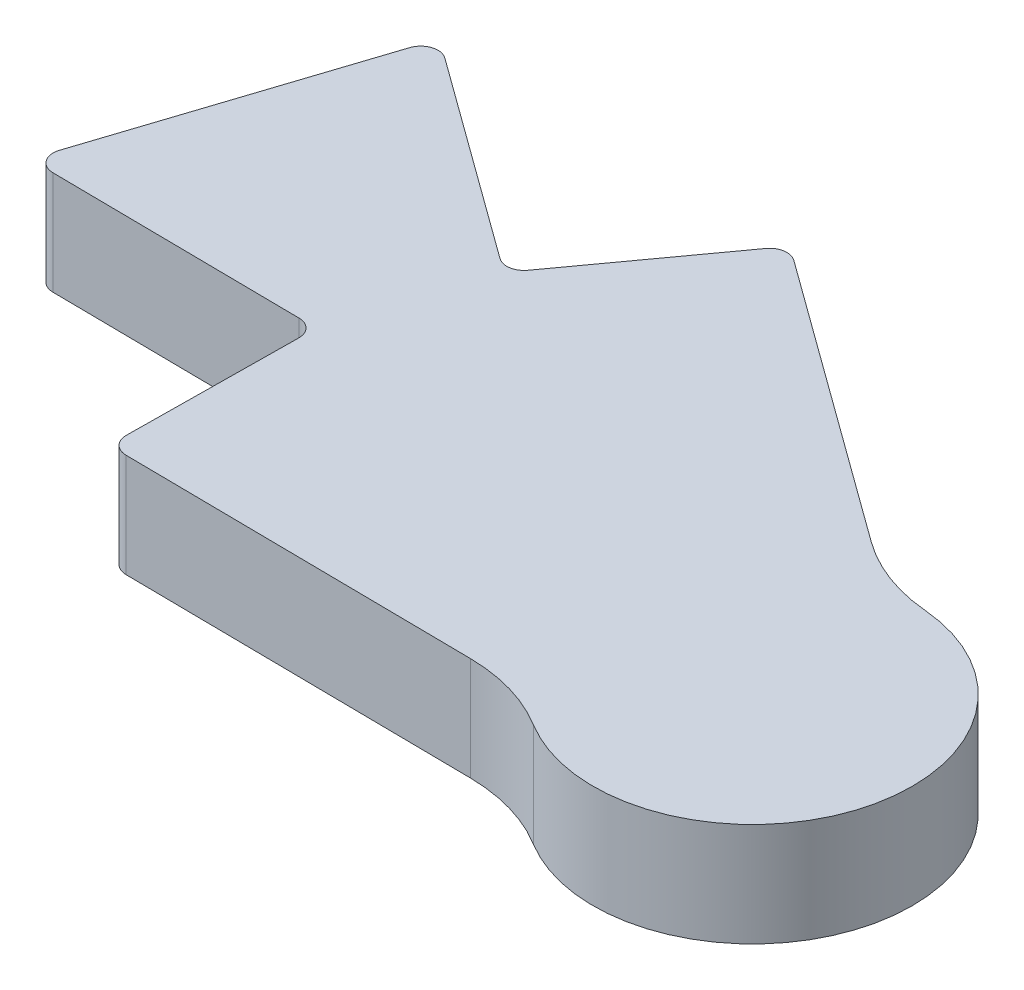
SolidWorks part; units mm, degrees
ref_plane "Front Plane" through (0, 0, 0) normal (0, 0, 1) x (1, 0, 0)
ref_plane "Top Plane" through (0, 0, 0) normal (0, 1, 0) x (1, 0, 0)
ref_plane "Right Plane" through (0, 0, 0) normal (1, 0, 0) x (0, 0, -1)
sketch "Sketch1" plane through (0, 0, 0) normal (0, 1, 0) x (1, 0, 0)
  line L19 (-46.373, 23.1103) -> (-64.9061, 36.5643)
  line L20 (-67.3478, 35.7723) -> (-75.2868, 11.4555)
  line L21 (-73.7956, 9.3754) -> (-50.877, 9.1163)
  line L22 (-49.3076, 7.511) -> (-49.4848, -8.1725)
  line L23 (-47.9154, -9.7778) -> (-15.8499, -10.1403)
  line L24 (-6.671, 17.5938) -> (-32.7243, 36.5071)
  line L25 (-34.9416, 36.155) -> (-44.1557, 23.4624)
  line L26 (-46.373, 23.1103) -> (-64.9061, 36.5643)
  line L27 (-67.3478, 35.7723) -> (-75.2868, 11.4555)
  line L28 (-73.7956, 9.3754) -> (-50.877, 9.1163)
  line L29 (-49.3076, 7.511) -> (-49.4848, -8.1725)
  line L30 (-47.9154, -9.7778) -> (-15.8499, -10.1403)
  line L31 (-6.671, 17.5938) -> (-32.7243, 36.5071)
  line L32 (-34.9416, 36.155) -> (-44.1557, 23.4624)
  circle A17 centre (0, 0) radius 14.6812 construction
  arc A18 (-7.7016, -12.4989) -> (1.2757, 14.6257) centre (0, 0) ccw
  arc A26 (-64.9061, 36.5643) -> (-67.3478, 35.7723) centre (-65.8387, 35.2796) ccw
  arc A27 (-75.2868, 11.4555) -> (-73.7956, 9.3754) centre (-73.7777, 10.9628) ccw
  arc A28 (-49.3076, 7.511) -> (-50.877, 9.1163) centre (-50.895, 7.5289) ccw
  arc A29 (-49.4848, -8.1725) -> (-47.9154, -9.7778) centre (-47.8974, -8.1904) ccw
  arc A30 (-7.7016, -12.4989) -> (-15.8499, -10.1403) centre (-16.0294, -26.0142) ccw
  arc A31 (1.2757, 14.6257) -> (-7.7016, -12.4989) centre (0, 0) ccw
  arc A32 (-6.671, 17.5938) -> (1.2757, 14.6257) centre (2.6551, 30.4406) ccw
  arc A33 (-32.7243, 36.5071) -> (-34.9416, 36.155) centre (-33.6569, 35.2224) ccw
  arc A34 (-46.373, 23.1103) -> (-44.1557, 23.4624) centre (-45.4404, 24.395) ccw
  arc A35 (-64.9061, 36.5643) -> (-67.3478, 35.7723) centre (-65.8387, 35.2796) ccw
  arc A36 (-75.2868, 11.4555) -> (-73.7956, 9.3754) centre (-73.7777, 10.9628) ccw
  arc A37 (-49.3076, 7.511) -> (-50.877, 9.1163) centre (-50.895, 7.5289) ccw
  arc A38 (-49.4848, -8.1725) -> (-47.9154, -9.7778) centre (-47.8974, -8.1904) ccw
  arc A39 (-7.7016, -12.4989) -> (-15.8499, -10.1403) centre (-16.0294, -26.0142) ccw
  arc A41 (-6.671, 17.5938) -> (1.2757, 14.6257) centre (2.6551, 30.4406) ccw
  arc A42 (-32.7243, 36.5071) -> (-34.9416, 36.155) centre (-33.6569, 35.2224) ccw
  arc A43 (-46.373, 23.1103) -> (-44.1557, 23.4624) centre (-45.4404, 24.395) ccw
  dimension "D1" = 0
extrude "Boss-Extrude1" add sketch "Sketch1" against normal up to surface (9.525 mm away)
